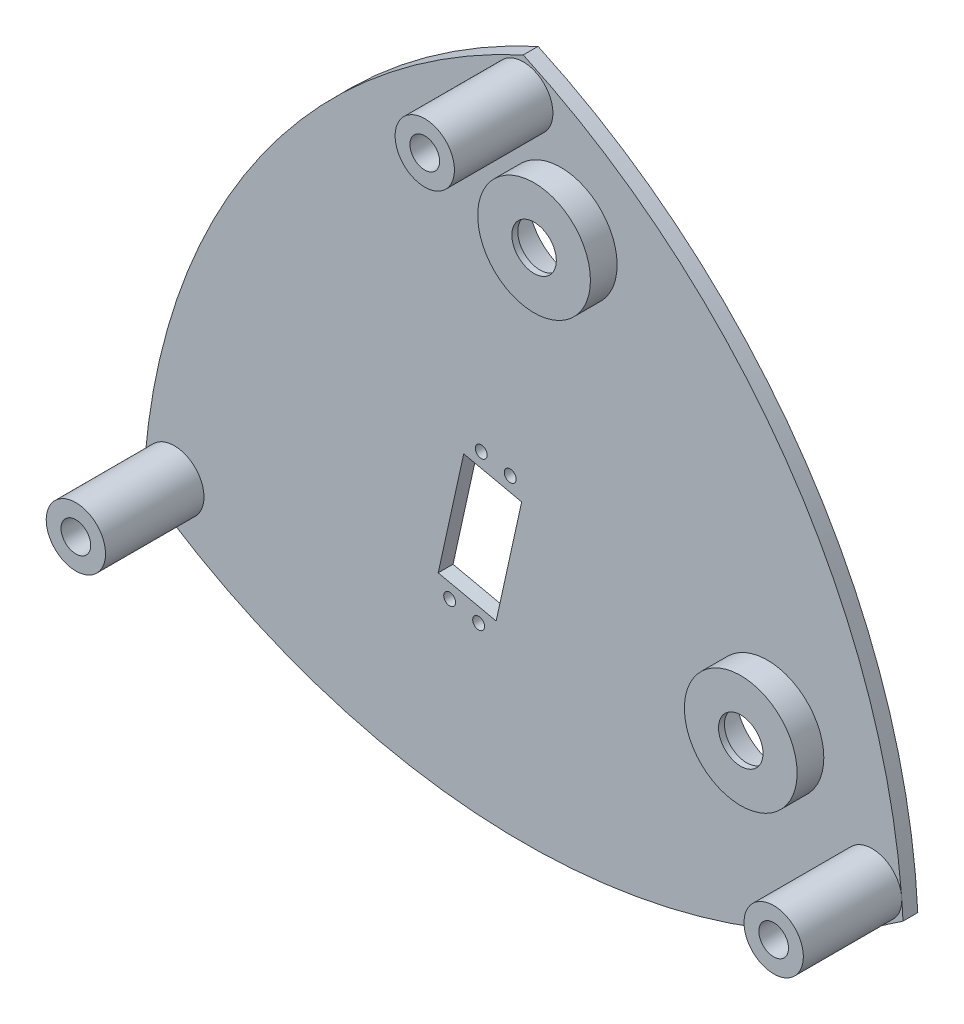
SolidWorks part; units mm, degrees
ref_plane "前视基准面" through (0, 0, 0) normal (0, 0, 1) x (1, 0, 0)
ref_plane "上视基准面" through (0, 0, 0) normal (0, 1, 0) x (1, 0, 0)
ref_plane "右视基准面" through (0, 0, 0) normal (1, 0, 0) x (0, 0, -1)
sketch "草图1" plane through (0, 0, 0) normal (0, 0, 1) x (1, 0, 0)
  line L0 (0, -115) -> (0, 115) construction
  line L2 (0, 0) -> (-128.0227, -73.9139) construction
  line L3 (0, 0) -> (128.0227, -73.9139) construction
  arc A5 (-128.0227, -73.9139) -> (0, 115) centre (91.6989, -84.9783) cw
  arc A6 (-128.0227, -73.9139) -> (128.0227, -73.9139) centre (0, 105) ccw
  arc A7 (128.0227, -73.9139) -> (0, 115) centre (-91.6989, -84.9783) ccw
  circle A8 centre (0, 103) radius 5
  circle A9 centre (-117.6304, -67.9139) radius 5
  circle A10 centre (117.6304, -67.9139) radius 5
  point P8 (-117.6304, -67.9139)
  point P11 (0, 103)
  point P12 (117.6304, -67.9139)
  dimension "D1" = 220
  dimension "D7" = 10
  dimension "D8" = 10
  dimension "D9" = 10
  dimension "D2" = 12
  dimension "D3" = 12
  dimension "D4" = 12
  dimension "D5" = 120
  dimension "D6" = 230
extrude "凸台-拉伸1" add sketch "草图1" along normal blind 5
sketch "草图2" plane through (0, 0, 5) normal (0, 0, 1) x (1, 0, 0)
  circle A0 centre (0, 103) radius 5
  circle A1 centre (0, 103) radius 10
  circle A2 centre (-117.6304, -67.9139) radius 5
  circle A3 centre (-117.6304, -67.9139) radius 10
  circle A4 centre (117.6304, -67.9139) radius 5
  circle A5 centre (117.6304, -67.9139) radius 10
  dimension "D1" = 20
  dimension "D2" = 20
  dimension "D3" = 20
extrude "凸台-拉伸2" add sketch "草图2" along normal blind 33.2
sketch "草图4" plane through (0, 0, 0) normal (0, 0, -1) x (-1, 0, 0)
  circle A0 centre (-12.651, 69.5155) radius 16
  circle A1 centre (-82.3341, -39.5307) radius 16
  dimension "D1" = 32
  dimension "D2" = 32
  dimension "D6" = 12.651
  dimension "D3" = 82.3341
  dimension "D4" = 39.5307
  dimension "D5" = 69.5155
extrude "切除-拉伸2" cut sketch "草图4" against normal blind 15
sketch "草图7" plane through (0, 0, 5) normal (0, 0, 1) x (1, 0, 0)
  circle A1 centre (82.3341, -39.5307) radius 19
  circle A3 centre (12.651, 69.5155) radius 19
  circle A5 centre (82.3341, -39.5307) radius 16
  circle A6 centre (12.651, 69.5155) radius 16
  dimension "D1" = 38
  dimension "D2" = 38
extrude "凸台-拉伸3" add sketch "草图7" along normal blind 7
sketch "草图8" plane through (0, 0, 12) normal (0, 0, 1) x (1, 0, 0)
  circle A1 centre (12.651, 69.5155) radius 7.5
  circle A3 centre (82.3341, -39.5307) radius 7.5
  circle A4 centre (82.3341, -39.5307) radius 19
  circle A5 centre (12.651, 69.5155) radius 19
  dimension "D1" = 15
  dimension "D2" = 15
extrude "凸台-拉伸4" add sketch "草图8" along normal blind 2
sketch "草图9" plane through (0, 0, 0) normal (0, 0, -1) x (-1, 0, 0)
  line L0 (20.0655, -11.4797) -> (28.6689, -50.5435)
  line L1 (28.6689, -50.5435) -> (9.137, -54.8452)
  line L2 (9.137, -54.8452) -> (0.5336, -15.7813)
  line L3 (0.5336, -15.7813) -> (20.0655, -11.4797)
extrude "切除-拉伸3" cut sketch "草图9" against normal blind 10
sketch "草图10" plane through (0, 0, 5) normal (0, 0, 1) x (1, 0, 0)
  circle A0 centre (-24.8075, -56.2577) radius 2
  circle A1 centre (-15.0416, -58.4086) radius 2
  circle A2 centre (-14.1609, -7.9163) radius 2
  circle A3 centre (-4.3949, -10.0671) radius 2
extrude "切除-拉伸4" cut sketch "草图10" against normal blind 10
